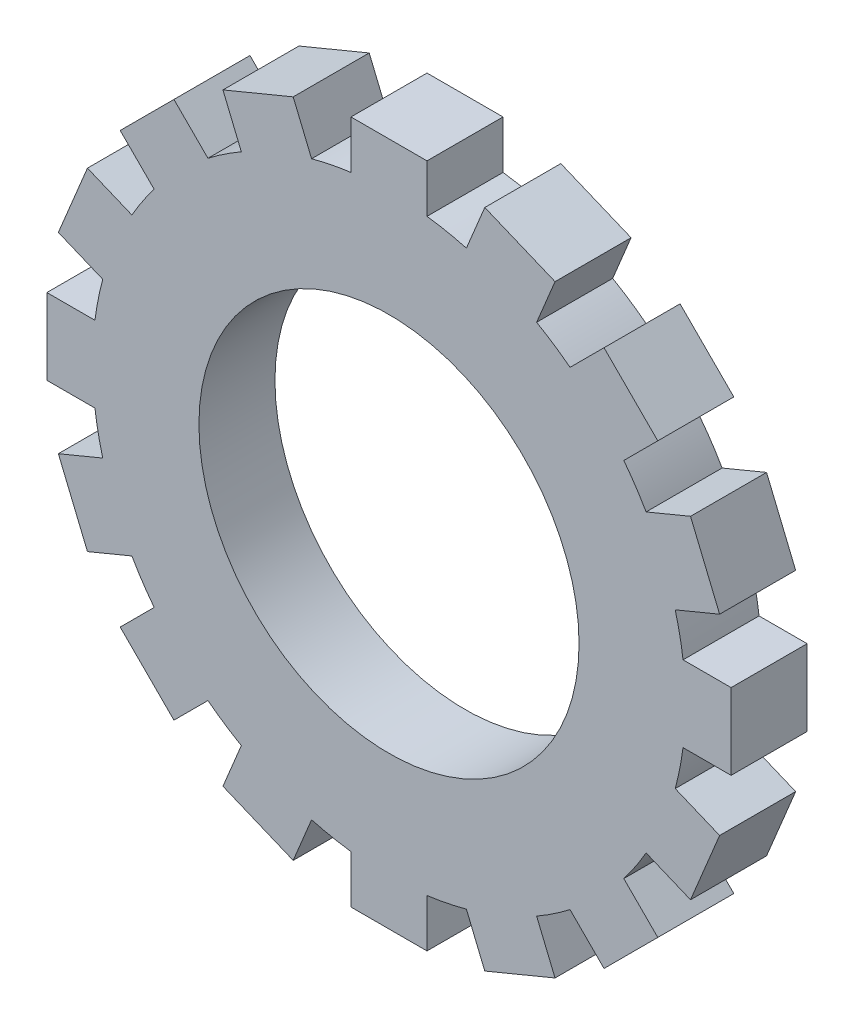
SolidWorks part; units mm, degrees
ref_plane "Ön Düzlem" through (0, 0, 0) normal (0, 0, 1) x (1, 0, 0)
ref_plane "Üst Düzlem" through (0, 0, 0) normal (0, 1, 0) x (1, 0, 0)
ref_plane "Sağ Düzlem" through (0, 0, 0) normal (1, 0, 0) x (0, 0, -1)
sketch "Çizim1" plane through (0, 0, 0) normal (0, 0, 1) x (1, 0, 0)
  line L0 (43.488, -12.6014) -> (39.6612, -21.8402)
  line L1 (33.8205, -19.4209) -> (39.6612, -21.8402)
  line L2 (37.6474, -10.1821) -> (43.488, -12.6014)
  line L3 (38.6782, 5) -> (45, 5)
  line L5 (38.6782, -5) -> (45, -5)
  line L6 (45, 5) -> (45, -5)
  line L7 (35.3553, -28.2843) -> (28.2843, -35.3553)
  line L8 (23.8141, -30.8851) -> (28.2843, -35.3553)
  line L9 (30.8851, -23.8141) -> (35.3553, -28.2843)
  line L10 (21.8402, -39.6612) -> (12.6014, -43.488)
  line L11 (10.1821, -37.6474) -> (12.6014, -43.488)
  line L12 (19.4209, -33.8205) -> (21.8402, -39.6612)
  line L13 (5, -45) -> (-5, -45)
  line L14 (-5, -38.6782) -> (-5, -45)
  line L15 (5, -38.6782) -> (5, -45)
  line L16 (-12.6014, -43.488) -> (-21.8402, -39.6612)
  line L17 (-19.4209, -33.8205) -> (-21.8402, -39.6612)
  line L18 (-10.1821, -37.6474) -> (-12.6014, -43.488)
  line L19 (-28.2843, -35.3553) -> (-35.3553, -28.2843)
  line L20 (-30.8851, -23.8141) -> (-35.3553, -28.2843)
  line L21 (-23.8141, -30.8851) -> (-28.2843, -35.3553)
  line L22 (-39.6612, -21.8402) -> (-43.488, -12.6014)
  line L23 (-37.6474, -10.1821) -> (-43.488, -12.6014)
  line L24 (-33.8205, -19.4209) -> (-39.6612, -21.8402)
  line L25 (-45, -5) -> (-45, 5)
  line L26 (-38.6782, 5) -> (-45, 5)
  line L27 (-38.6782, -5) -> (-45, -5)
  line L28 (-43.488, 12.6014) -> (-39.6612, 21.8402)
  line L29 (-33.8205, 19.4209) -> (-39.6612, 21.8402)
  line L30 (-37.6474, 10.1821) -> (-43.488, 12.6014)
  line L31 (-35.3553, 28.2843) -> (-28.2843, 35.3553)
  line L32 (-23.8141, 30.8851) -> (-28.2843, 35.3553)
  line L33 (-30.8851, 23.8141) -> (-35.3553, 28.2843)
  line L34 (-21.8402, 39.6612) -> (-12.6014, 43.488)
  line L35 (-10.1821, 37.6474) -> (-12.6014, 43.488)
  line L36 (-19.4209, 33.8205) -> (-21.8402, 39.6612)
  line L37 (-5, 45) -> (5, 45)
  line L38 (5, 38.6782) -> (5, 45)
  line L39 (-5, 38.6782) -> (-5, 45)
  line L40 (12.6014, 43.488) -> (21.8402, 39.6612)
  line L41 (19.4209, 33.8205) -> (21.8402, 39.6612)
  line L42 (10.1821, 37.6474) -> (12.6014, 43.488)
  line L43 (28.2843, 35.3553) -> (35.3553, 28.2843)
  line L44 (30.8851, 23.8141) -> (35.3553, 28.2843)
  line L45 (23.8141, 30.8851) -> (28.2843, 35.3553)
  line L46 (39.6612, 21.8402) -> (43.488, 12.6014)
  line L47 (37.6474, 10.1821) -> (43.488, 12.6014)
  line L48 (33.8205, 19.4209) -> (39.6612, 21.8402)
  circle A0 centre (0, 0) radius 25
  arc A1 (-30.8851, 23.8141) -> (-33.8205, 19.4209) centre (0, 0) ccw
  circle A2 centre (0, 0) radius 45 construction
  arc A3 (-19.4209, 33.8205) -> (-23.8141, 30.8851) centre (0, 0) ccw
  arc A4 (-5, 38.6782) -> (-10.1821, 37.6474) centre (0, 0) ccw
  arc A5 (10.1821, 37.6474) -> (5, 38.6782) centre (0, 0) ccw
  arc A6 (23.8141, 30.8851) -> (19.4209, 33.8205) centre (0, 0) ccw
  arc A7 (38.6782, 5) -> (37.6474, 10.1821) centre (0, 0) ccw
  arc A8 (37.6474, -10.1821) -> (38.6782, -5) centre (0, 0) ccw
  arc A9 (30.8851, -23.8141) -> (33.8205, -19.4209) centre (0, 0) ccw
  arc A10 (19.4209, -33.8205) -> (23.8141, -30.8851) centre (0, 0) ccw
  arc A11 (5, -38.6782) -> (10.1821, -37.6474) centre (0, 0) ccw
  arc A12 (-10.1821, -37.6474) -> (-5, -38.6782) centre (0, 0) ccw
  arc A13 (-23.8141, -30.8851) -> (-19.4209, -33.8205) centre (0, 0) ccw
  arc A14 (-33.8205, -19.4209) -> (-30.8851, -23.8141) centre (0, 0) ccw
  arc A15 (-38.6782, -5) -> (-37.6474, -10.1821) centre (0, 0) ccw
  arc A16 (-37.6474, 10.1821) -> (-38.6782, 5) centre (0, 0) ccw
  arc A17 (33.8205, 19.4209) -> (30.8851, 23.8141) centre (0, 0) ccw
  point P1 (0, 0)
  point P3 (0, 0)
  point P4 (0, 0)
  point P7 (0, 0)
  dimension "D1" = 50
  dimension "D2" = 78
  dimension "D3" = 90
  dimension "D4" = 16
extrude "Yükseklik-Ekstrüzyon2" add sketch "Çizim1" along normal blind 10
